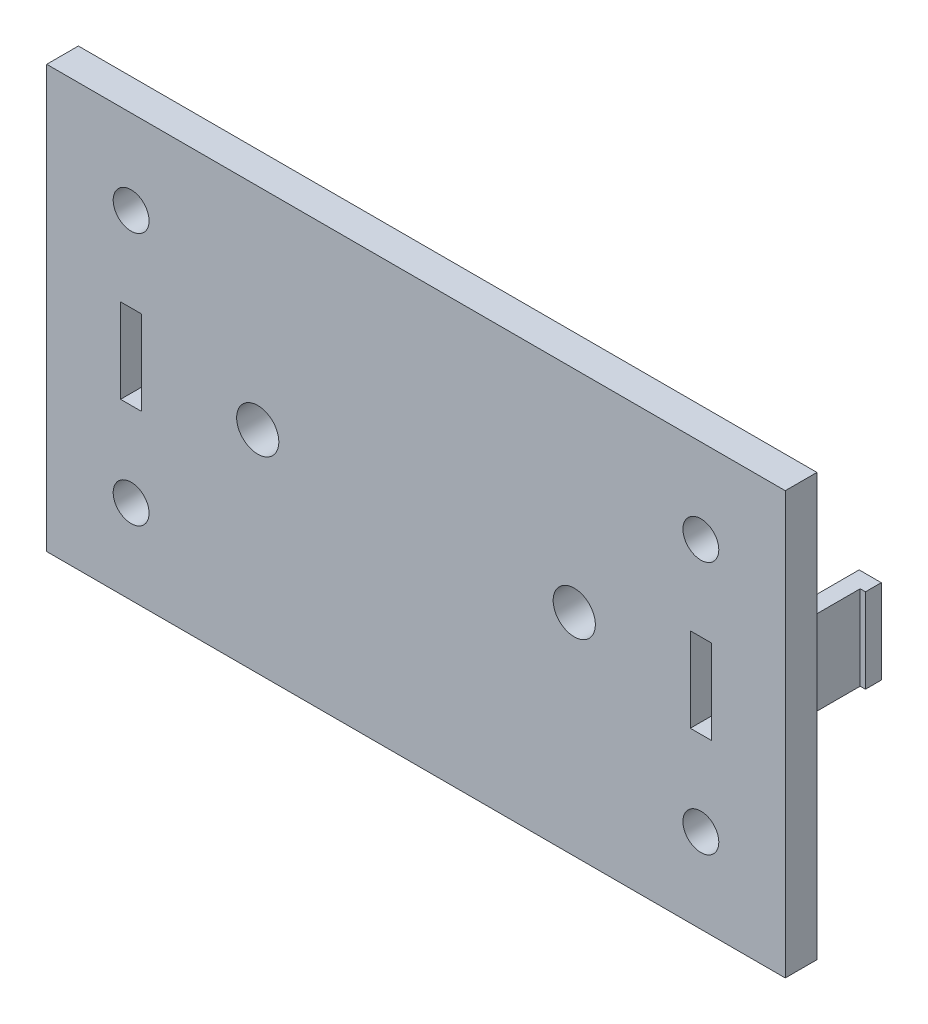
SolidWorks part; units mm, degrees
ref_plane "Front Plane" through (0, 0, 0) normal (0, 0, 1) x (1, 0, 0)
ref_plane "Top Plane" through (0, 0, 0) normal (0, 1, 0) x (1, 0, 0)
ref_plane "Right Plane" through (0, 0, 0) normal (1, 0, 0) x (0, 0, -1)
other "Configuration Table"
sketch "Sketch2" plane through (0, 0, 0) normal (0, 0, 1) x (1, 0, 0)
  line L1 (-35, -20) -> (35, -20)
  line L2 (-35, -20) -> (-35, 20)
  line L3 (-35, 20) -> (35, 20)
  line L4 (35, -20) -> (35, 20)
extrude "Lid_plate" add sketch "Sketch2" along normal blind 3 from offset 0
sketch "Sketch3" plane through (0, 0, 0) normal (0, 0, 1) x (1, 0, 0)
  circle A0 centre (-15, 0) radius 2
extrude "Port_bore" cut sketch "Sketch3" along normal blind 3 from offset 0
sketch "Sketch4" plane through (0, 0, 0) normal (0, 0, 1) x (1, 0, 0)
  circle A0 centre (15, 0) radius 2
extrude "Cut-Extrude2" cut sketch "Sketch4" along normal blind 3 from offset 0
sketch "Sketch5" plane through (0, 0, 0) normal (0, 0, 1) x (1, 0, 0)
  circle A0 centre (-27, -12) radius 1.7
extrude "Screw_clearance" cut sketch "Sketch5" along normal blind 3 from offset 0
sketch "Sketch6" plane through (0, 0, 0) normal (0, 0, 1) x (1, 0, 0)
  circle A0 centre (-27, 12) radius 1.7
extrude "Cut-Extrude4" cut sketch "Sketch6" along normal blind 3 from offset 0
sketch "Sketch7" plane through (0, 0, 0) normal (0, 0, 1) x (1, 0, 0)
  circle A0 centre (27, -12) radius 1.7
extrude "Cut-Extrude5" cut sketch "Sketch7" along normal blind 3 from offset 0
sketch "Sketch8" plane through (0, 0, 0) normal (0, 0, 1) x (1, 0, 0)
  circle A0 centre (27, 12) radius 1.7
extrude "Cut-Extrude6" cut sketch "Sketch8" along normal blind 3 from offset 0
sketch "Sketch9" plane through (0, 0, 0) normal (0, 0, 1) x (1, 0, 0)
  line L1 (-30.6, -4) -> (-29, -4)
  line L2 (-30.6, -4) -> (-30.6, 4)
  line L3 (-30.6, 4) -> (-29, 4)
  line L4 (-29, -4) -> (-29, 4)
extrude "Snap_beam" add sketch "Sketch9" along normal blind 10 from offset 10
sketch "Sketch10" plane through (0, 0, 0) normal (0, 0, 1) x (1, 0, 0)
  line L1 (-31.1, -4) -> (-30.6, -4)
  line L2 (-31.1, -4) -> (-31.1, 4)
  line L3 (-31.1, 4) -> (-30.6, 4)
  line L4 (-30.6, -4) -> (-30.6, 4)
extrude "Snap_hook" add sketch "Sketch10" along normal blind 1.5 from offset 10
sketch "Sketch11" plane through (0, 0, 0) normal (0, 0, 1) x (1, 0, 0)
  line L1 (-28, -4) -> (-26, -4)
  line L2 (-28, -4) -> (-28, 4)
  line L3 (-28, 4) -> (-26, 4)
  line L4 (-26, -4) -> (-26, 4)
extrude "Snap_release_access" cut sketch "Sketch11" along normal blind 3 from offset 0
sketch "Sketch12" plane through (0, 0, 0) normal (0, 0, 1) x (1, 0, 0)
  line L1 (29, -4) -> (30.6, -4)
  line L2 (29, -4) -> (29, 4)
  line L3 (29, 4) -> (30.6, 4)
  line L4 (30.6, -4) -> (30.6, 4)
extrude "Boss-Extrude4" add sketch "Sketch12" along normal blind 10 from offset 10
sketch "Sketch13" plane through (0, 0, 0) normal (0, 0, 1) x (1, 0, 0)
  line L1 (30.6, -4) -> (31.1, -4)
  line L2 (30.6, -4) -> (30.6, 4)
  line L3 (30.6, 4) -> (31.1, 4)
  line L4 (31.1, -4) -> (31.1, 4)
extrude "Boss-Extrude5" add sketch "Sketch13" along normal blind 1.5 from offset 10
sketch "Sketch14" plane through (0, 0, 0) normal (0, 0, 1) x (1, 0, 0)
  line L1 (26, -4) -> (28, -4)
  line L2 (26, -4) -> (26, 4)
  line L3 (26, 4) -> (28, 4)
  line L4 (28, -4) -> (28, 4)
extrude "Cut-Extrude8" cut sketch "Sketch14" along normal blind 3 from offset 0
